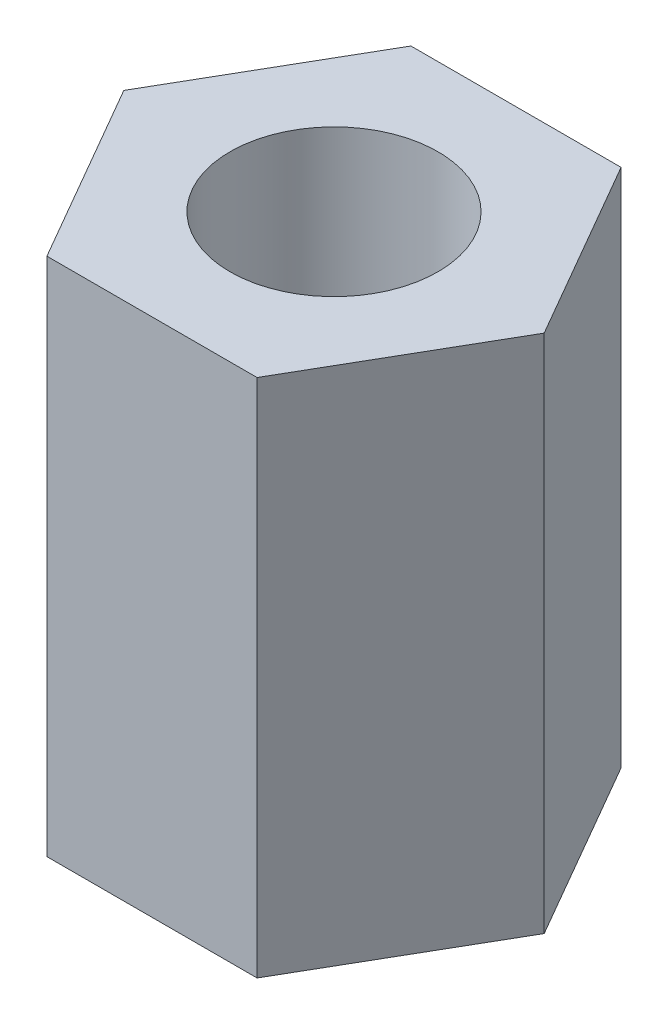
SolidWorks part; units mm, degrees
material "黄铜"
ref_plane "前视基准面" through (0, 0, 0) normal (0, 0, 1) x (1, 0, 0)
ref_plane "上视基准面" through (0, 0, 0) normal (0, 1, 0) x (1, 0, 0)
ref_plane "右视基准面" through (0, 0, 0) normal (1, 0, 0) x (0, 0, -1)
sketch "草图1" plane through (0, 0, 0) normal (0, 1, 0) x (1, 0, 0)
  line L1 (4.0415, 0) -> (2.0207, 3.5)
  line L2 (2.0207, 3.5) -> (-2.0207, 3.5)
  line L3 (-2.0207, 3.5) -> (-4.0415, 0)
  line L4 (-4.0415, 0) -> (-2.0207, -3.5)
  line L5 (-2.0207, -3.5) -> (2.0207, -3.5)
  line L6 (2.0207, -3.5) -> (4.0415, 0)
  circle A0 centre (0, 0) radius 3.5 construction
  circle A1 centre (0, 0) radius 2
  dimension "D1" = 4
  dimension "D2" = 7
extrude "凸台-拉伸1" add sketch "草图1" along normal blind 10
